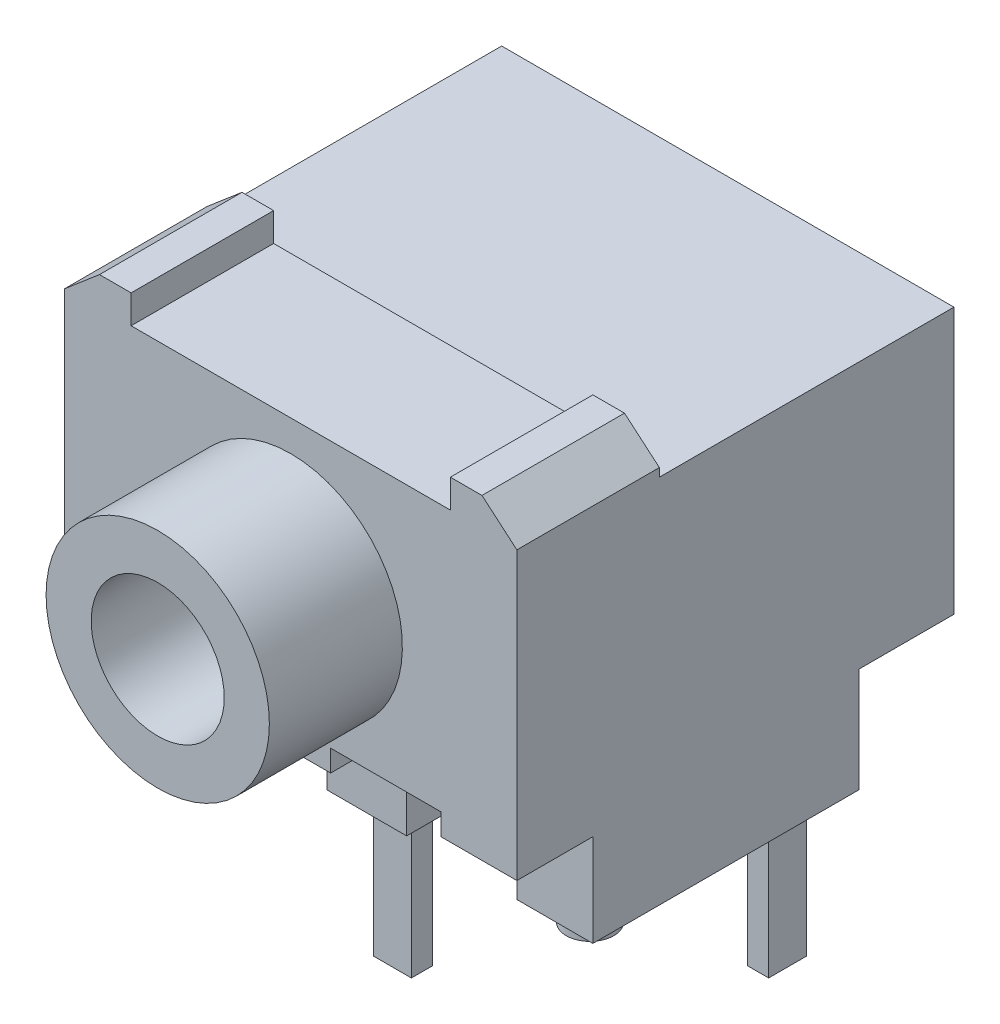
SolidWorks part; units mm, degrees
ref_plane "front" through (0, 0, 0) normal (0, 0, 1) x (1, 0, 0)
ref_plane "top" through (0, 0, 0) normal (0, 1, 0) x (1, 0, 0)
ref_plane "right" through (0, 0, 0) normal (1, 0, 0) x (0, 0, -1)
sketch "Sketch2" plane through (0, 0, 0) normal (1, 0, 0) x (0, 0, -1)
  line L0 (2.032, 0) -> (9.144, 0)
  line L5 (9.144, 0) -> (9.144, 2.794)
  line L6 (9.144, 2.794) -> (11.684, 2.794)
  line L7 (11.684, 2.794) -> (11.684, 9.906)
  line L8 (11.684, 9.906) -> (3.81, 9.906)
  line L9 (3.81, 9.906) -> (3.81, 10.9728)
  line L10 (3.81, 10.9728) -> (0, 10.9728)
  line L11 (0, 10.9728) -> (0, 2.4716)
  line L12 (0, 2.4716) -> (2.032, 2.4716)
  line L13 (2.032, 2.4716) -> (2.032, 0)
  dimension "D5" = 3.81
  dimension "D7" = 10.9728
  dimension "D8" = 9.906
  dimension "D9" = 2.794
  dimension "D10" = 2.032
  dimension "D11" = 9.144
extrude "Extrude2" add sketch "Sketch2" along normal mid plane 12.7
sketch "Sketch3" plane through (0, 0, 0) normal (0, 0, 1) x (1, 0, 0)
  line L0 (-4.0117, 0) -> (-6.0452, 0)
  line L8 (6.0452, 10.1285) -> (5.1126, 10.922)
  line L9 (4.0117, 0) -> (6.0452, 0)
  line L10 (6.0452, 0) -> (6.0452, 10.1285)
  line L11 (0, -4.5777) -> (0, -7.1976) construction
  line L12 (5.1126, 10.922) -> (4.2672, 10.922)
  line L13 (4.2672, 10.922) -> (4.2672, 10.16)
  line L14 (4.2672, 10.16) -> (-4.2672, 10.16)
  line L15 (1.0668, 3.048) -> (1.0668, 0)
  line L16 (1.0668, 0) -> (-1.0668, 0)
  line L19 (4.0117, 0) -> (4.0117, 3.048)
  line L20 (4.0117, 3.048) -> (1.0668, 3.048)
  line L22 (-4.0117, 3.048) -> (-1.0668, 3.048)
  line L23 (-4.0117, 0) -> (-4.0117, 3.048)
  line L26 (-1.0668, 3.048) -> (-1.0668, 0)
  line L27 (-4.2672, 10.922) -> (-4.2672, 10.16)
  line L28 (-5.1126, 10.922) -> (-4.2672, 10.922)
  line L29 (-6.0452, 0) -> (-6.0452, 10.1285)
  line L31 (-6.0452, 10.1285) -> (-5.1126, 10.922)
  circle A2 centre (0, 3.9878) radius 3.302 construction
  dimension "D4" = 12.0904
  dimension "D6" = 6.604
  dimension "D7" = 3.9878
  dimension "D8" = 1.778
  dimension "D9" = 0.762
  dimension "D10" = 3.048
  dimension "D15" = 10.922
extrude "Cut-Extrude1" cut sketch "Sketch3" against normal through all flip side to cut
sketch "Sketch6" plane through (0, 0, 0) normal (0, 0, 1) x (1, 0, 0)
  circle A0 centre (0, 6.35) radius 2.9845
  circle A1 centre (0, 6.35) radius 1.778
  dimension "D1" = 5.969
  dimension "D3" = 3.556
  dimension "D2" = 6.35
extrude "Extrude4" add sketch "Sketch6" along normal blind 3.556
sketch "Sketch7" plane through (0, 0, 0) normal (0, 1, 0) x (1, 0, 0)
  circle A0 centre (0, 8.001) radius 0.635
  circle A1 centre (5.0038, 2.9972) radius 0.635
  circle A2 centre (-5.0038, 2.9972) radius 0.635
  dimension "D5" = 1.27
  dimension "D1" = 2.9972
  dimension "D2" = 5.0038
  dimension "D3" = 5.0038
  dimension "D4" = 5.0038
extrude "Extrude5" add sketch "Sketch7" against normal blind 0.508
sketch "Sketch8" plane through (0, 0, 0) normal (0, 1, 0) x (1, 0, 0)
  line L0 (0, 5.1756) -> (0, 6.5053) construction
  line L1 (-0.508, 2.7178) -> (0.508, 2.7178)
  line L2 (-0.508, 2.7178) -> (-0.508, 3.2766)
  line L3 (-0.508, 3.2766) -> (0.508, 3.2766)
  line L4 (0.508, 2.7178) -> (0.508, 3.2766)
  line L5 (-5.2832, 7.493) -> (-5.2832, 8.509)
  line L6 (-4.7244, 8.509) -> (-5.2832, 8.509)
  line L7 (-4.7244, 7.493) -> (-4.7244, 8.509)
  line L8 (-4.7244, 7.493) -> (-5.2832, 7.493)
  line L9 (4.7244, 7.493) -> (5.2832, 7.493)
  line L10 (4.7244, 7.493) -> (4.7244, 8.509)
  line L11 (4.7244, 8.509) -> (5.2832, 8.509)
  line L12 (5.2832, 7.493) -> (5.2832, 8.509)
  point P12 (0, 2.7178)
  point P13 (0.508, 2.9972)
  point P15 (5.0038, 7.493)
  point P16 (5.2832, 8.001)
  dimension "D1" = 0.5588
  dimension "D2" = 1.016
  dimension "D3" = 2.9972
  dimension "D4" = 5.0038
  dimension "D5" = 5.0038
extrude "Extrude6" add sketch "Sketch8" against normal blind 3.9116
